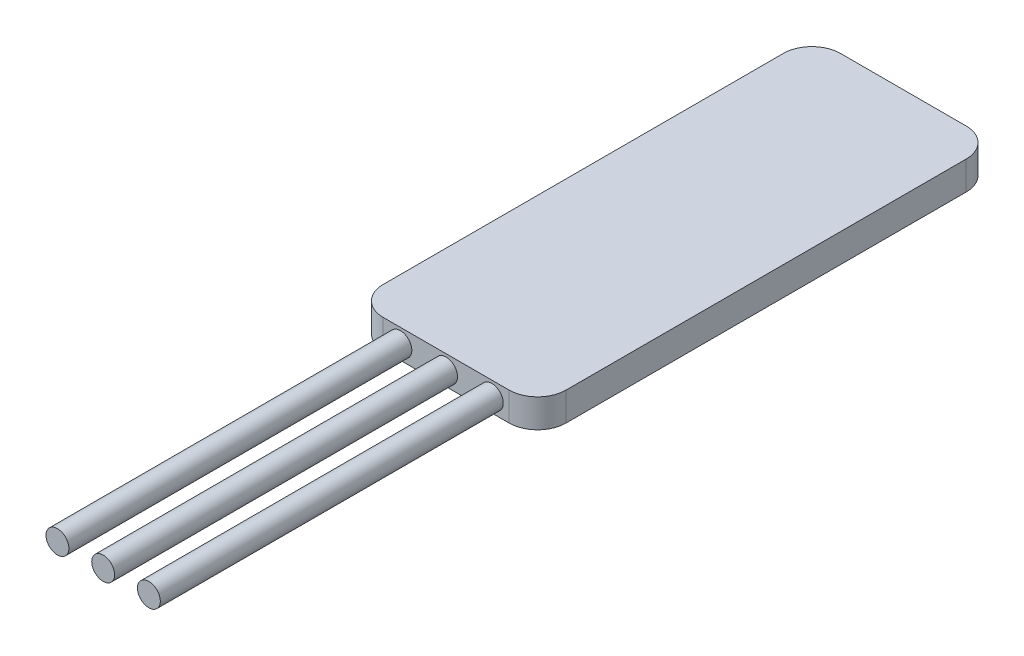
SolidWorks part; units mm, degrees
material "Silicon Rubber"
ref_plane "Front Plane" through (0, 0, 0) normal (0, 0, 1) x (1, 0, 0)
ref_plane "Top Plane" through (0, 0, 0) normal (0, 1, 0) x (1, 0, 0)
ref_plane "Right Plane" through (0, 0, 0) normal (1, 0, 0) x (0, 0, -1)
sketch "Sketch1" plane through (0, 0, 0) normal (0, 1, 0) x (1, 0, 0)
  line L1 (-3.2, 8) -> (3.2, 8)
  line L2 (-3.2, 8) -> (-3.2, -8)
  line L3 (-3.2, -8) -> (3.2, -8)
  line L4 (3.2, 8) -> (3.2, -8)
  line L5 (-3.2, 8) -> (3.2, -8) construction
  line L6 (-3.2, -8) -> (3.2, 8) construction
  point P0 (0, 0)
  dimension "D1" = 16
  dimension "D2" = 6.4
extrude "BASE" add sketch "Sketch1" along normal mid plane 1
fillet "BF" radius 1 4 edges at (-3.2, 0, -8) (3.2, 0, -8) (-3.2, 0, 8) (3.2, 0, 8)
sketch "Sketch2" plane through (0, 0, 8) normal (0, 0, 1) x (1, 0, 0)
  circle A0 centre (0, 0) radius 0.4
  dimension "D1" = 0.8
extrude "WIRE" add sketch "Sketch2" along normal blind 12
pattern_linear "WIRE LP" count 2 spacing 1.6 along (-1, 0, 0) count 2 spacing 1.6 along (1, 0, 0) of "WIRE"
